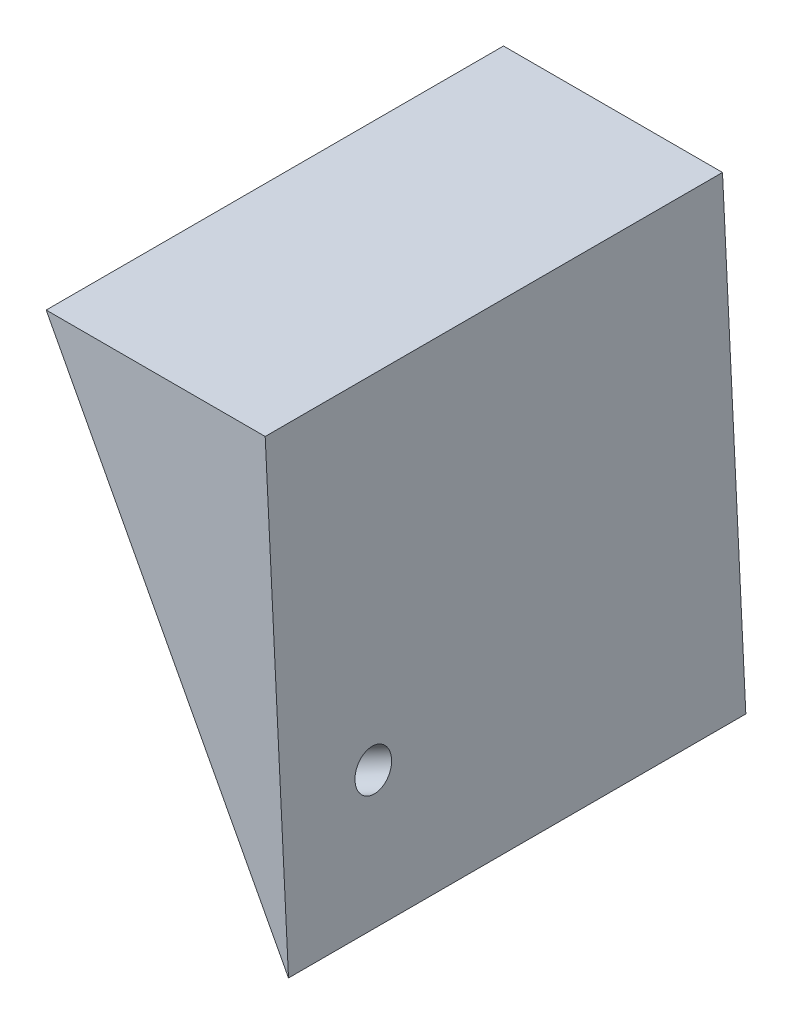
SolidWorks part; units mm, degrees
ref_plane "Front Plane" through (0, 0, 0) normal (0, 0, 1) x (1, 0, 0)
ref_plane "Top Plane" through (0, 0, 0) normal (0, 1, 0) x (1, 0, 0)
ref_plane "Right Plane" through (0, 0, 0) normal (1, 0, 0) x (0, 0, -1)
sketch "Sketch1" plane through (0, 0, 0) normal (0, 0, 1) x (1, 0, 0)
  line L0 (-36.2386, 19.2413) -> (-9.7428, -30.7587)
  line L1 (-9.7428, -30.7587) -> (-12.2931, 19.2413)
  line L2 (-12.2931, 19.2413) -> (-36.2386, 19.2413)
  dimension "D1" = 50
  dimension "D2" = 50
  dimension "D3" = 25
extrude "Boss-Extrude1" add sketch "Sketch1" along normal blind 50
sketch "Sketch2" plane through (-20.3326, -10.7746, 0) normal (-0.8836, -0.4682, 0) x (0, 0, 1)
  line L0 (50, 33.97) -> (50, -22.6165) construction
  line L1 (50, -22.6165) -> (0, -22.6165) construction
  circle A0 centre (40, -9.6165) radius 2
  dimension "D1" = 4
  dimension "D2" = 10
  dimension "D3" = 13
extrude "Cut-Extrude1" cut sketch "Sketch2" against normal blind 50
